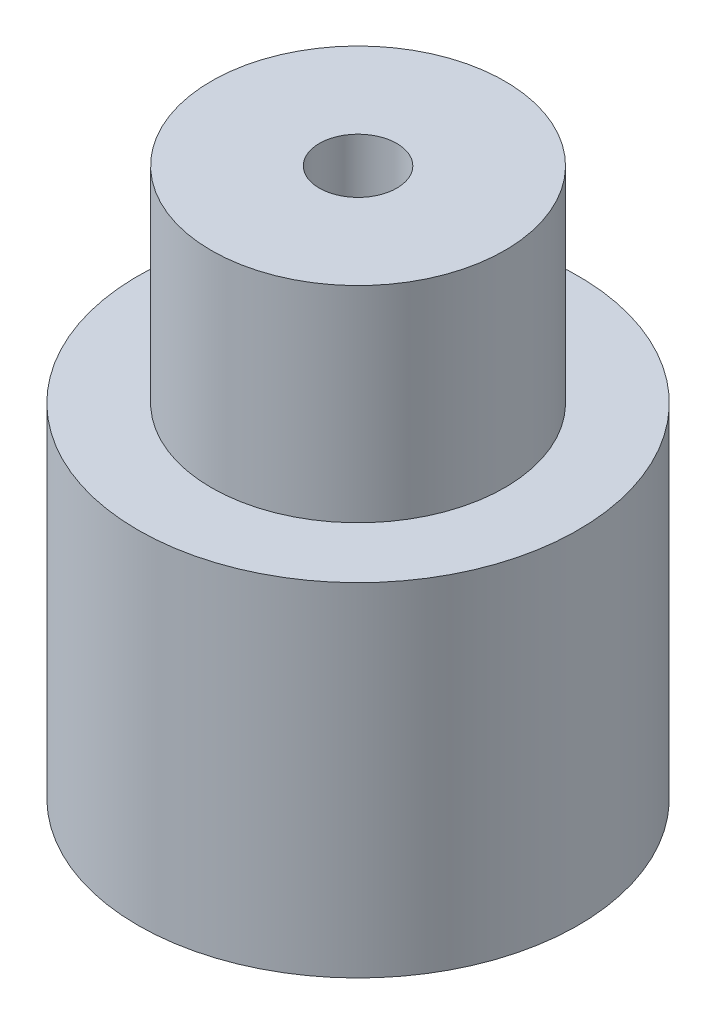
SolidWorks part; units mm, degrees
ref_plane "前视基准面" through (0, 0, 0) normal (0, 0, 1) x (1, 0, 0)
ref_plane "上视基准面" through (0, 0, 0) normal (0, 1, 0) x (1, 0, 0)
ref_plane "右视基准面" through (0, 0, 0) normal (1, 0, 0) x (0, 0, -1)
sketch "草图1" plane through (0, 0, 0) normal (0, 1, 0) x (1, 0, 0)
  circle A0 centre (0, 0) radius 9
extrude "凸台-拉伸1" add sketch "草图1" along normal blind 14
sketch "草图2" plane through (0, 14, 0) normal (0, 1, 0) x (1, 0, 0)
  circle A0 centre (0, 0) radius 6
extrude "凸台-拉伸2" add sketch "草图2" along normal blind 8.4
sketch "草图4" plane through (0, 22.4, 0) normal (0, 1, 0) x (1, 0, 0)
  circle A0 centre (0, 0) radius 1.585
extrude "切除-拉伸1" cut sketch "草图4" against normal up to next
